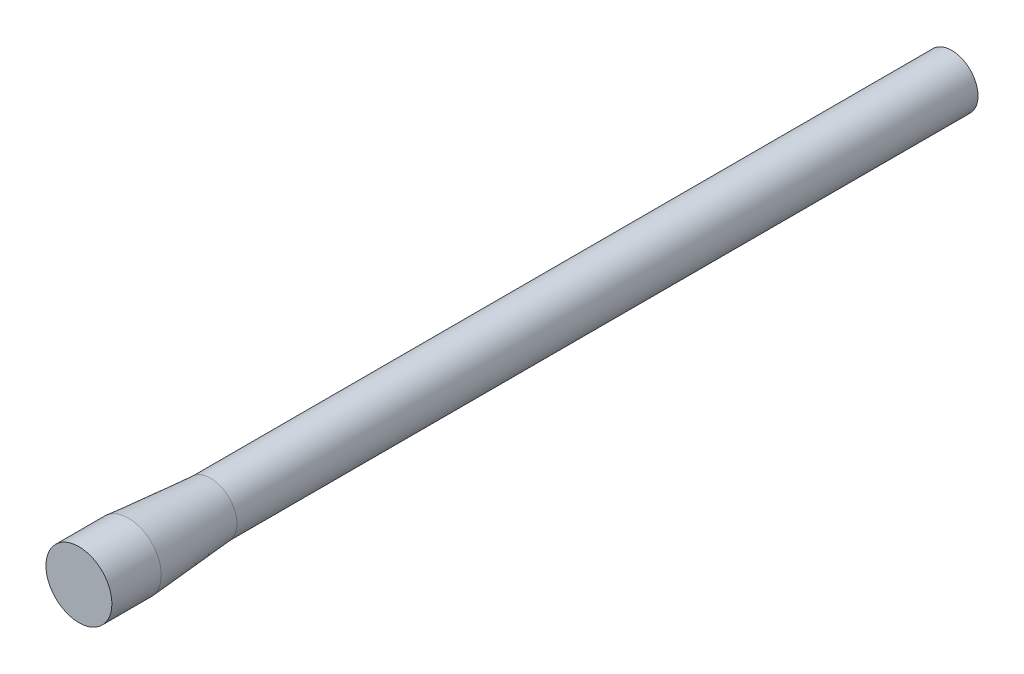
SolidWorks part; units mm, degrees
ref_plane "Piano frontale" through (0, 0, 0) normal (1, 0, 0) x (0, 1, 0)
ref_plane "Piano superiore" through (0, 0, 0) normal (0, 0, 1) x (0, 1, 0)
ref_plane "Piano destro" through (0, 0, 0) normal (0, 1, 0) x (-1, 0, 0)
sketch "Schizzo1" plane through (0, 0, 0) normal (0, 0, 1) x (0, 1, 0)
  circle A0 centre (0, 0) radius 1.6
  dimension "D1" = 3.2
extrude "Estrusione-Estrusione1" add sketch "Schizzo1" along normal blind 45
sketch "Schizzo2" plane through (0, 0, 45) normal (0, 0, 1) x (1, 0, 0)
  circle A0 centre (0, 0) radius 1.6
extrude "Estrusione-Estrusione2" add sketch "Schizzo2" along normal blind 5 draft 4.6 draft outward yes
sketch "Schizzo3" plane through (0, 0, 50) normal (0, 0, 1) x (1, 0, 0)
  circle A0 centre (0, 0) radius 2.0023
extrude "Estrusione-Estrusione3" add sketch "Schizzo3" along normal blind 3
